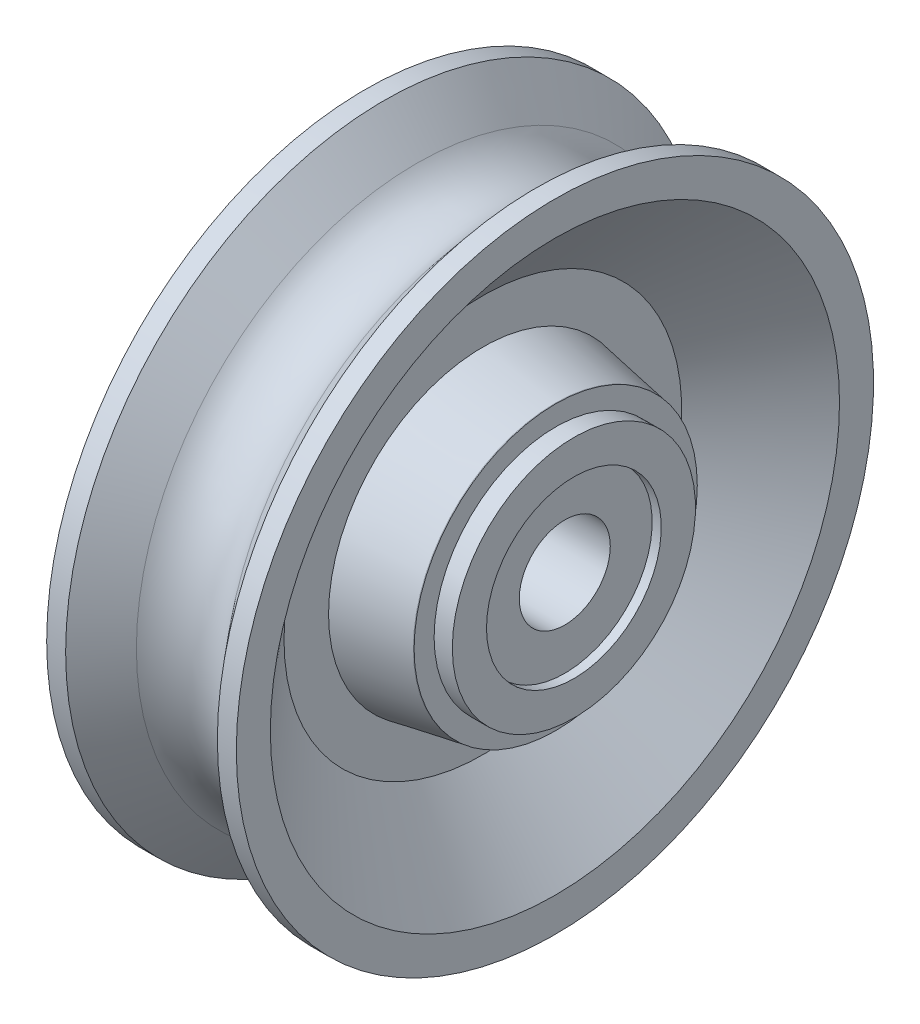
SolidWorks part; units mm, degrees
ref_plane "Front Plane" through (0, 0, 0) normal (0, 0, 1) x (1, 0, 0)
ref_plane "Top Plane" through (0, 0, 0) normal (0, 1, 0) x (1, 0, 0)
ref_plane "Right Plane" through (0, 0, 0) normal (1, 0, 0) x (0, 0, -1)
sketch "Sketch1" plane through (0, 0, 0) normal (0, 0, 1) x (1, 0, 0)
  line L0 (5.2917, 22.225) -> (6.6146, 22.225)
  line L1 (-5.2917, 22.225) -> (-6.6146, 22.225)
  line L2 (-5.2917, 22.225) -> (-3.0379, 19.5441)
  line L3 (7.9375, 9.8778) -> (7.9375, 3.175)
  line L4 (7.9375, 3.175) -> (-7.9375, 3.175)
  line L5 (-7.9375, 3.175) -> (-7.9375, 9.8778)
  line L6 (5.2917, 22.225) -> (3.0379, 19.5441)
  line L7 (-7.9375, 9.8778) -> (-6.6146, 9.8778)
  line L8 (-7.9375, 0) -> (7.9375, 0) construction
  line L9 (-6.6146, 9.8778) -> (-6.6146, 22.225)
  line L10 (6.6146, 22.225) -> (6.6146, 9.8778)
  line L11 (6.6146, 9.8778) -> (7.9375, 9.8778)
  arc A0 (-3.0379, 19.5441) -> (3.0379, 19.5441) centre (0, 22.098) ccw
  circle A1 centre (0, 22.098) radius 3.9688 construction
  circle A2 centre (0, -22.098) radius 3.9688 construction
  dimension "Rope Dia" = 7.9375
  dimension "Width" = 15.875
  dimension "Shaft Dia" = 6.35
  dimension "OD" = 44.45
  dimension "A" = 36.2585
  dimension "D1" = 19.7556
  dimension "D2" = 2.6458
  dimension "D3" = 1.3229
revolve "Revolve1" add sketch "Sketch1" angle 360 about L8
sketch "Sketch2" plane through (0, 0, 0) normal (0, 0, 1) x (1, 0, 0)
  line L0 (-7.9375, 9.8778) -> (-6.6146, 9.8778)
  line L1 (-6.6146, 9.8778) -> (-1.5875, 10.7642)
  line L2 (-1.5875, 10.7642) -> (-1.5875, 13.8718)
  line L3 (-1.5875, 13.8718) -> (-7.9375, 21.4251)
  line L6 (-5.2917, 22.225) -> (-3.0379, 19.5441) construction
  line L7 (-7.9375, 9.8778) -> (-7.9375, 21.4251)
  line L8 (0, 0) -> (0, 22.098) construction
  line L9 (7.9375, 9.8778) -> (7.9375, 21.4251)
  line L10 (1.5875, 13.8718) -> (7.9375, 21.4251)
  line L11 (1.5875, 10.7642) -> (1.5875, 13.8718)
  line L12 (6.6146, 9.8778) -> (1.5875, 10.7642)
  line L13 (7.9375, 9.8778) -> (6.6146, 9.8778)
  dimension "D1" = 2.54
  dimension "D2" = 3.175
  dimension "D4" = 3.1076
  dimension "D3" = 10
revolve "Cut-Revolve1" cut sketch "Sketch2" angle 360 about L8
sketch "Sketch3" plane through (0, 0, 0) normal (1, 0, 0) x (0, 0, -1)
  line L0 (0, 13.8718) -> (0, 10.7642) construction
  circle A0 centre (0, 12.318) radius 0.7769
  dimension "D2" = 1.5538
  dimension "D1" = 3.1076
extrude "Cut-Extrude1" [suppressed] cut sketch "Sketch3" against normal through all and the other way through all
pattern_circular "CirPattern1" [suppressed] count 8 over 360
sketch "Sketch4" plane through (-7.9375, 0, 0) normal (-1, 0, 0) x (0, 0, 1)
  circle A2 centre (0, 0) radius 8.4808
  circle A3 centre (0, 0) radius 8.4808
  circle A5 centre (0, 0) radius 11.7828
  circle A6 centre (0, 0) radius 11.7828
  dimension "D1" = 1.397
  dimension "D2" = 1.905
extrude "Cut-Extrude2" cut sketch "Sketch4" against normal blind 1.27
sketch "Sketch5" plane through (-7.9375, 0, 0) normal (-1, 0, 0) x (0, 0, 1)
  circle A2 centre (0, 0) radius 6.096
  circle A3 centre (0, 0) radius 6.096
  dimension "D1" = 2.921
extrude "Cut-Extrude3" cut sketch "Sketch5" against normal blind 0.635
mirror "Mirror1" about plane through (0, 0, 0) normal (1, 0, 0) of "Cut-Extrude3", "Cut-Extrude2"
equation "\"D1@Sketch1\" = \"OD@Sketch1\"/2.250"
equation "\"D2@Sketch1\" = \"Width@Sketch1\"/6"
equation "\"D3@Sketch1\" = \"D2@Sketch1\"/2"
equation "\"D2@Sketch2\" = \"Width@Sketch1\"/5"
equation "\"D1@Sketch3\" = \"D4@Sketch2\""
equation "\"D2@Sketch3\" = \"D1@Sketch3\"*.5"
